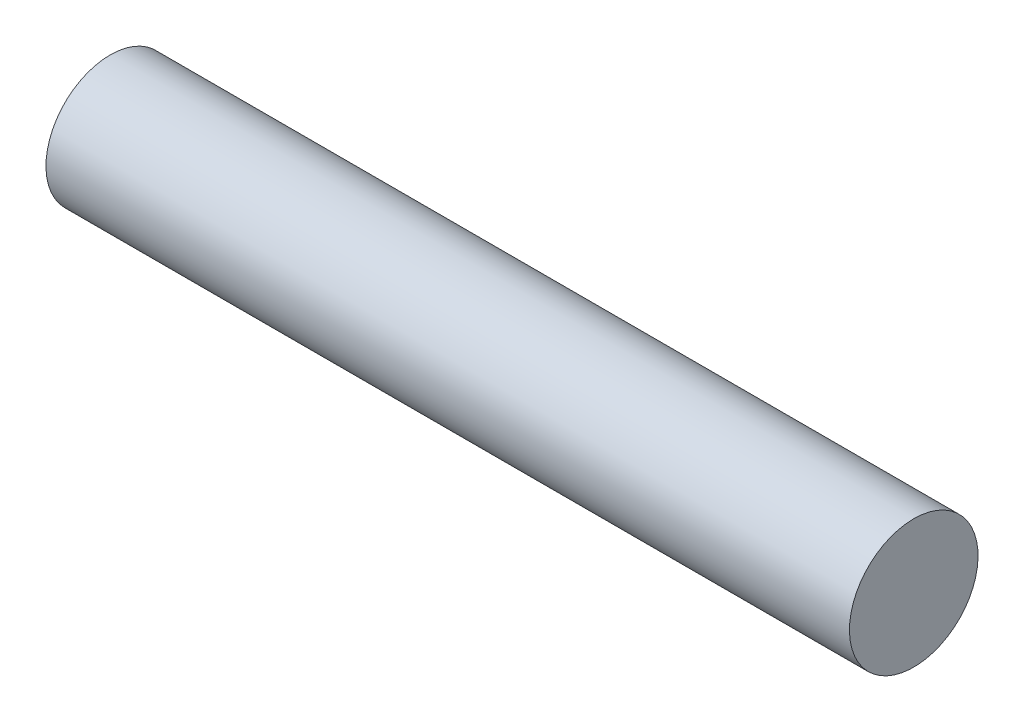
SolidWorks part; units mm, degrees
ref_plane "Front Plane" through (0, 0, 0) normal (0, 0, 1) x (1, 0, 0)
ref_plane "Top Plane" through (0, 0, 0) normal (0, 1, 0) x (1, 0, 0)
ref_plane "Right Plane" through (0, 0, 0) normal (1, 0, 0) x (0, 0, -1)
sketch "Sketch1" plane through (0, 0, 0) normal (0, 0, 1) x (1, 0, 0)
  line L1 (0, 0) -> (-175, 0)
  line L2 (0, 0) -> (0, -14)
  line L3 (0, -14) -> (-175, -14)
  line L4 (-175, 0) -> (-175, -14)
  dimension "D1" = 175
  dimension "D2" = 14
revolve "Revolve2" add sketch "Sketch1" angle 360 about L3
